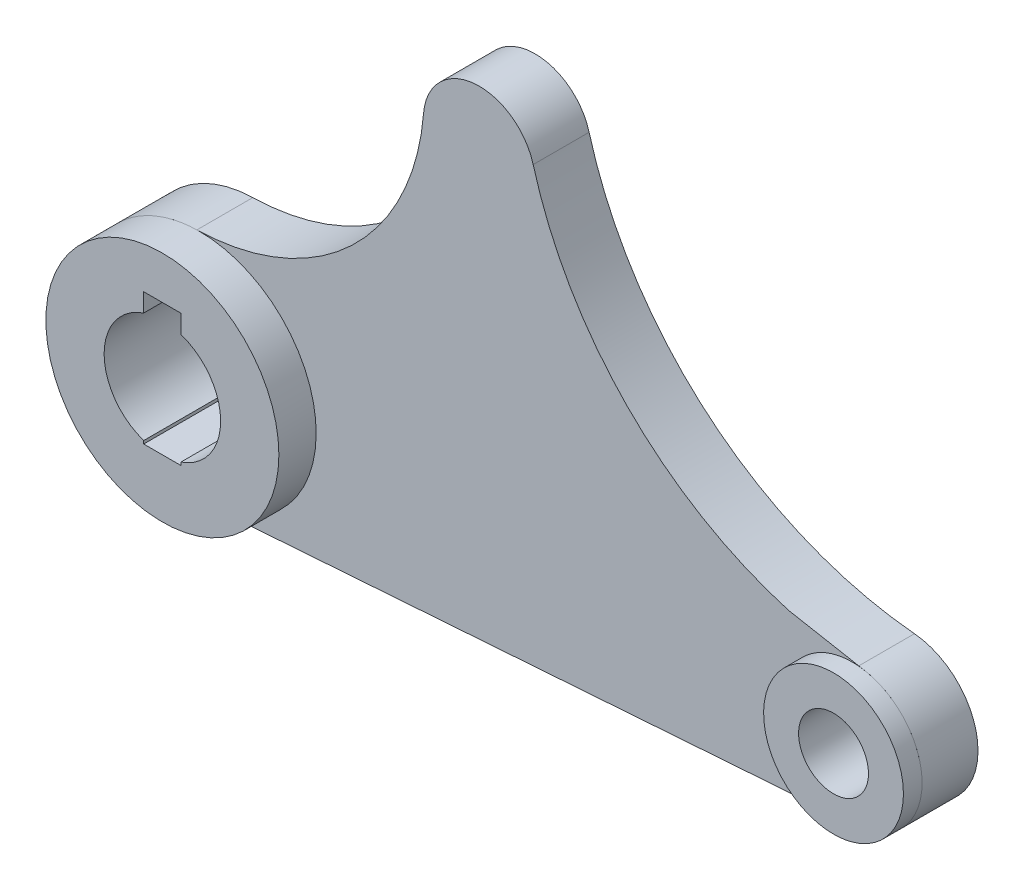
SolidWorks part; units mm, degrees
ref_plane "前视基准面" through (0, 0, 0) normal (0, 0, 1) x (1, 0, 0)
ref_plane "上视基准面" through (0, 0, 0) normal (0, 1, 0) x (1, 0, 0)
ref_plane "右视基准面" through (0, 0, 0) normal (1, 0, 0) x (0, 0, -1)
sketch "草图1" plane through (0, 0, 0) normal (0, 0, 1) x (1, 0, 0)
  line L0 (1.7857, -24.9361) -> (141.0714, -14.9617)
  arc A0 (141.0714, -14.9617) -> (141.366, 14.938) centre (139.9998, 0.0002) ccw
  arc A1 (141.366, 14.938) -> (71.563, 73.209) centre (148.6496, 94.6072) cw
  arc A2 (71.563, 73.209) -> (48.0395, 70.9631) centre (60.0004, 70.0005) ccw
  arc A3 (48.0395, 70.9631) -> (-0.5987, 24.992) centre (-1.7968, 74.9752) cw
  arc A4 (-0.5987, 24.992) -> (1.7857, -24.9361) centre (0.0004, -0.0004) ccw
extrude "凸台-拉伸1" add sketch "草图1" along normal blind 12
ref_plane "基准面1" through (0, 0, 12) normal (0, 0, 1) x (1, 0, 0)
sketch "草图2" plane through (0, 0, 12) normal (0, 0, 1) x (1, 0, 0)
  circle A0 centre (0, 0) radius 25
extrude "凸台-拉伸2" add sketch "草图2" along normal blind 8
sketch "草图3" plane through (0, 0, 12) normal (0, 0, 1) x (1, 0, 0)
  circle A0 centre (140, 0) radius 15
extrude "凸台-拉伸3" add sketch "草图3" along normal blind 4
ref_plane "基准面2" through (0, 0, 20) normal (0, 0, 1) x (1, 0, 0)
sketch "草图4" plane through (0, 0, 20) normal (0, 0, 1) x (1, 0, 0)
  circle A0 centre (0, 0) radius 12.5
extrude "切除-拉伸1" cut sketch "草图4" against normal through all
ref_plane "基准面3" through (0, 0, 16) normal (0, 0, 1) x (1, 0, 0)
sketch "草图5" plane through (0, 0, 16) normal (0, 0, 1) x (1, 0, 0)
  circle A0 centre (140, 0) radius 7.5
extrude "切除-拉伸2" cut sketch "草图5" against normal mid plane 362
sketch "草图6" plane through (0, 0, 12) normal (0, 0, 1) x (1, 0, 0)
  circle A0 centre (60, 70) radius 5
extrude "切除-拉伸3" cut sketch "草图6" against normal mid plane 362
sketch "草图7" plane through (0, 0, 20) normal (0, 0, 1) x (1, 0, 0)
  line L0 (-4, -12.5) -> (4, -12.5)
  line L1 (4, -12.5) -> (4, 15.8)
  line L2 (4, 15.8) -> (-4, 15.8)
  line L3 (-4, 15.8) -> (-4, -12.5)
extrude "切除-拉伸4" cut sketch "草图7" against normal mid plane 362
sketch "草图8" plane through (0, 0, 12) normal (0, 0, 1) x (1, 0, 0)
  arc A0 (74.3392, 15.8013) -> (64.4517, 40.2739) centre (-0.0023, -0.0007) ccw
  arc A1 (64.4517, 40.2739) -> (57.6673, 36.0345) centre (61.0595, 38.1542) ccw
  arc A2 (57.6673, 36.0345) -> (66.514, 14.138) centre (0.0016, 0.0008) cw
  arc A3 (66.514, 14.138) -> (74.3392, 15.8013) centre (70.4244, 14.9798) ccw
extrude "切除-拉伸5" cut sketch "草图8" against normal mid plane 362
